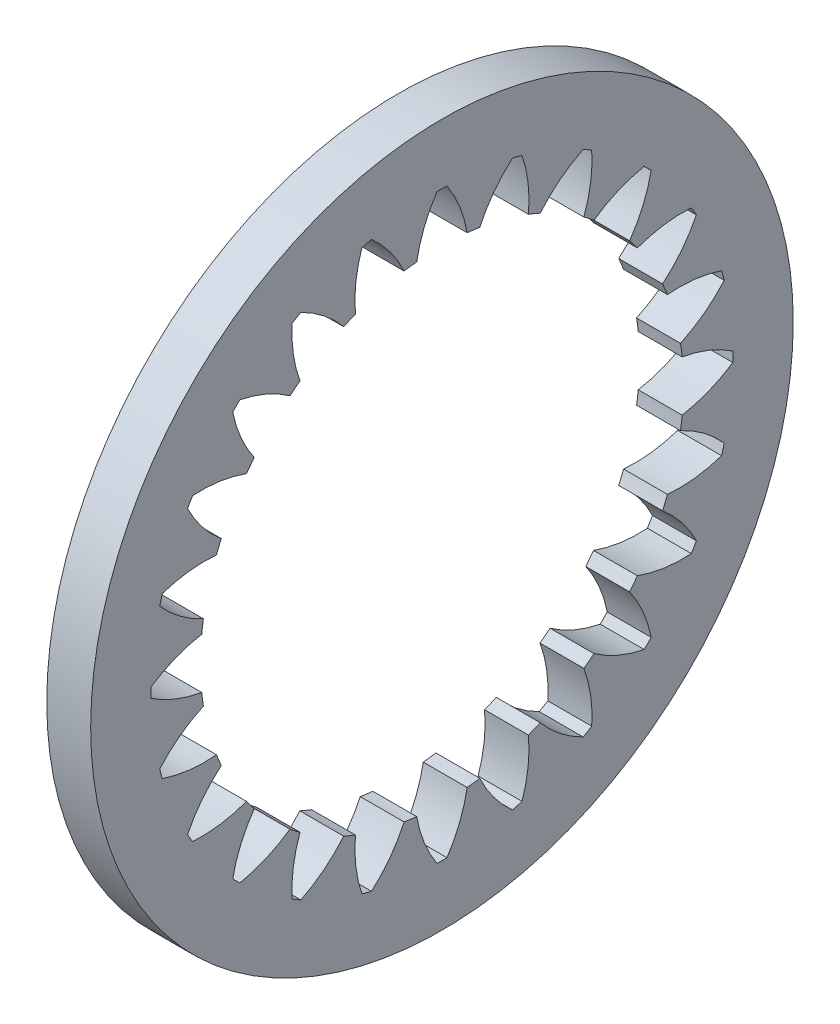
SolidWorks part; units mm, degrees
ref_plane "Plane1" through (0, 0, 0) normal (0, 0, 1) x (1, 0, 0)
ref_plane "Plane2" through (0, 0, 0) normal (0, 1, 0) x (1, 0, 0)
ref_plane "Plane3" through (0, 0, 0) normal (1, 0, 0) x (0, 0, -1)
sketch "HoldingSke" plane through (0, 0, 0) normal (0, 1, 0) x (1, 0, 0)
  line L0 (0, 0) -> (-17.6427, -100.0565)
  line L1 (-15, 0) -> (100, 0) construction
  line L2 (0, 0) -> (-2.1039, 2.3779)
  line L3 (0, 0) -> (-11.863, 4.5341)
  line L4 (0, 0) -> (7.8894, 3.5126)
  line L5 (0, 0) -> (-23.7986, -8.8762)
  line L6 (0, 0) -> (-10.5278, -7.1032)
  line L7 (-2.1039, 2.3779) -> (3.3635, 27.1825)
  line L8 (-76.2, 54.61) -> (-54.61, 54.61)
  line L9 (-67.7845, 28.3722) -> (-49.3413, 33.142)
  line L10 (-76.2, 71.12) -> (104.1128, 71.12)
  line L11 (0, 0) -> (-12.7, 0)
  line L12 (-76.2, 101.6) -> (-75.9714, 101.6)
  line L13 (24.9733, 27.94) -> (52.9518, 28.4284)
  line L14 (24.9733, 27.94) -> (24.9746, 27.94)
  line L15 (24.9733, 27.94) -> (100.4006, 29.5858)
  circle A0 centre (0, 0) radius 101.6
  circle A1 centre (0, 0) radius 12.7
  circle A2 centre (0, 0) radius 12.7
  dimension "MHD" = 25.4
  dimension "Hub_dia" = 25.4
  dimension "Diameter" = 203.2
  dimension "Num_teeth" = 24
  dimension "Pitch" = 101.6
  dimension "Overall_len" = 25.4
  dimension "Show_teeth" = 100
  dimension "Thickness" = 12.7
  dimension "OAL" = 25.4001
  dimension "T_dim" = 21.59
  dimension "Ap" = 14.5
  dimension "H" = 19.05
  dimension "Pitch_radius" = 180.3128
  dimension "Width" = 12.7
  dimension "Backlash" = 0.2286
  dimension "Addendum_fac" = 1
  dimension "Dedendum_fac" = 1.25
  dimension "Clearance_fac" = 0.25
  dimension "Dedendum_add" = 0.0013
sketch "BasProSke" plane through (0, 0, 0) normal (0, 1, 0) x (1, 0, 0)
  line L0 (-10, 0) -> (60, 0) construction
  line L1 (0, 69.85) -> (0, 101.6)
  line L2 (0, 69.85) -> (12.7, 69.85)
  line L3 (12.7, 69.85) -> (12.7, 101.6)
  line L4 (12.7, 101.6) -> (0, 101.6)
  dimension "Diameter" = 203.2
  dimension "Thickness" = 12.7
  dimension "Inside_diameter" = 139.7
revolve "Base-Revolve" add sketch "BasProSke" angle 360 about L0
sketch "TooCutSke" plane through (0, 0, 0) normal (1, 0, 0) x (0, 0, -1)
  line L3 (5.5552, 75.9972) -> (5.5552, 53.6633) construction
  line L4 (0, 0) -> (0, 59.563) construction
  line L5 (0, 0) -> (-8.9185, 67.7429) construction
  line L6 (-30.2541, 62.9855) -> (28.8527, 70.767) construction
  circle A0 centre (0, 0) radius 76.2 construction
  circle A1 centre (0, 0) radius 84.1388 construction
  circle A2 centre (0, 0) radius 66.3956 construction
  circle A3 centre (0, 0) radius 69.8246 construction
  arc A4 (7.2948, 69.4425) -> (1.4425, 84.1264) centre (-30.2541, 62.9855) ccw
  arc A5 (7.2948, 69.4425) -> (-7.2948, 69.4425) centre (0, 0) ccw
  arc A6 (1.4425, 84.1264) -> (-1.4425, 84.1264) centre (0, 0) ccw
  arc A7 (-1.4425, 84.1264) -> (-7.2948, 69.4425) centre (30.2541, 62.9855) ccw
  dimension "Pitch_dia" = 152.4
  dimension "Base_dia" = 132.7911
  dimension "Root_dia" = 168.2775
  dimension "Overcut_dia" = 139.6492
  dimension "Flank_rad" = 38.1
  dimension "Half_ang" = 7.5
  dimension "Half_CT" = 5.5552
extrude "ToothCut" cut sketch "TooCutSke" along normal through all
fillet "Breaks" [suppressed] radius 0.635
fillet "RootFillets" [suppressed] radius 1.5888
pattern_circular "TeethCuts" count 24 every 15 about axis through (-10, 0, 0) along (1, 0, 0) of "RootFillets", "Breaks", "ToothCut"
equation "' \"Pitch@HoldingSke\" = 4"
equation "' \"Num_teeth@HoldingSke\" = 24"
equation "' \"Ap@HoldingSke\" =  14.5"
equation "' \"Ap@HoldingSke\" = 14.5"
equation "' \"Width@HoldingSke\" = 0.5"
equation "' \"Diameter@HoldingSke\" = 8"
equation "' \"Show_teeth@HoldingSke\" = 100"
equation "' \"Backlash@HoldingSke\" = 0.009"
equation "' \"Addendum_fac@HoldingSke\" = 1.0"
equation "' \"Dedendum_fac@HoldingSke\" = 1.25"
equation "' \"Dedendum_add@HoldingSke\" = 0.00005"
equation "' \"Clearance_fac@HoldingSke\" = 0.25"
equation "\"Overcut_dia@TooCutSke\" = (\"Num_teeth@HoldingSke\" - 2 * \"Addendum_fac@HoldingSke\") / \"Pitch@HoldingSke\" - 0.002"
equation "\"Pitch_dia@TooCutSke\" = \"Num_teeth@HoldingSke\" / \"Pitch@HoldingSke\""
equation "\"Base_dia@TooCutSke\" = \"Num_teeth@HoldingSke\" / \"Pitch@HoldingSke\" * cos((\"Ap@HoldingSke\"  * 3.14159265 / 180)) * 0.90"
equation "\"Root_dia@TooCutSke\" = \"Num_teeth@HoldingSke\"  / \"Pitch@HoldingSke\" + 2 *  \"Dedendum_fac@HoldingSke\"/ \"Pitch@HoldingSke\" + \"Dedendum_add@HoldingSke\" * 2"
equation "\"Half_ang@TooCutSke\" = 180 / \"Num_teeth@HoldingSke\""
equation "\"Half_CT@TooCutSke\" = \"Num_teeth@HoldingSke\" / \"Pitch@HoldingSke\" * sin((3.14159265 / 2 / \"Num_teeth@HoldingSke\")) / 2 + 10 * \"Backlash@HoldingSke\" / 4"
equation "\"Flank_rad@TooCutSke\" = \"Num_teeth@HoldingSke\" / \"Pitch@HoldingSke\" / 4"
equation "\"Radius@RootFillets\"= \"Clearance_fac@HoldingSke\" / \"Pitch@HoldingSke\" + \"Dedendum_add@HoldingSke\""
equation "\"Break_rad@Breaks\" = 0.02 / \"Pitch@HoldingSke\" * 5"
equation "\"Num_teeth@TeethCuts\" = int( \"Show_teeth@HoldingSke\" ) + 1"
equation "\"Num_teeth@TeethCuts\" = ((sgn( \"Num_teeth@TeethCuts\" - \"Num_teeth@HoldingSke\" )-1)*( \"Num_teeth@TeethCuts\" - \"Num_teeth@HoldingSke\" ))/-2+ \"Num_teeth@HoldingSke\""
equation "\"Num_teeth@TeethCuts\" = ((sgn( \"Num_teeth@TeethCuts\" - 2.0)+1)*( \"Num_teeth@TeethCuts\" - 2.0))/2 +2.0"
equation "\"Angle@TeethCuts\" = 360.0 / \"Num_teeth@HoldingSke\""
equation "\"Diameter@BasProSke\" = \"Num_teeth@HoldingSke\"  / \"Pitch@HoldingSke\" + 2 *  \"Dedendum_fac@HoldingSke\"/ \"Pitch@HoldingSke\" + \"Dedendum_add@HoldingSke\" * 2 + 0.002"
equation "\"Diameter@BasProSke\" = ((sgn( \"Diameter@BasProSke\"  - \"Diameter@HoldingSke\" )+1)*( \"Diameter@BasProSke\"  - \"Diameter@HoldingSke\" ))/2 + \"Diameter@HoldingSke\""
equation "\"Inside_diameter@BasProSke\" =  (\"Num_teeth@HoldingSke\" - 2 * \"Addendum_fac@HoldingSke\") / \"Pitch@HoldingSke\" "
equation "\"Thickness@BasProSke\"  = \"Width@HoldingSke\""
